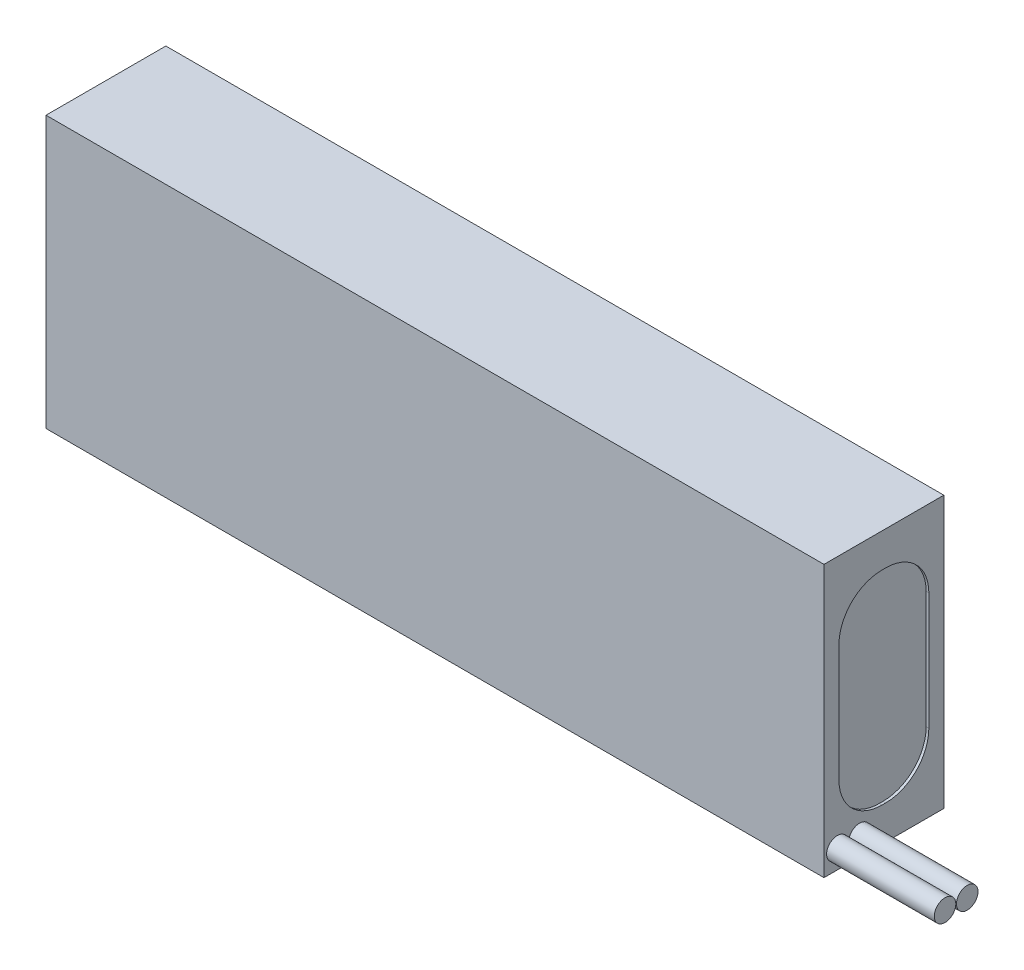
SolidWorks part; units mm, degrees
ref_plane "Front Plane" through (0, 0, 0) normal (0, 0, 1) x (1, 0, 0)
ref_plane "Top Plane" through (0, 0, 0) normal (0, 1, 0) x (1, 0, 0)
ref_plane "Right Plane" through (0, 0, 0) normal (1, 0, 0) x (0, 0, -1)
ref_plane "Plane1" through (0, 0, -15) normal (0, 0, -1) x (-1, 0, 0)
sketch "Sketch1" plane through (0, 0, -15) normal (0, 0, -1) x (-1, 0, 0)
  line L0 (-69, -22) -> (75.5, -22)
  line L1 (75.5, -22) -> (75.5, 28.4)
  line L2 (75.5, 28.4) -> (-69, 28.4)
  line L3 (-69, 28.4) -> (-69, -22)
  line L4 (-69, 3.2) -> (75.5, 3.2) construction
  line L5 (3.25, 28.4) -> (3.25, -22) construction
  dimension "D1" = 50.4
  dimension "D2" = 144.5
extrude "Boss-Extrude1" add sketch "Sketch1" against normal blind 22.26
sketch "Sketch2" plane through (69, 0, 0) normal (1, 0, 0) x (0, 0, -1)
  line L0 (-4.4775, 14.1) -> (-4.4775, -7.7)
  line L1 (3.5225, -15.7) -> (4.2175, -15.7)
  line L2 (12.2175, -7.7) -> (12.2175, 14.1)
  line L3 (4.2175, 22.1) -> (3.5225, 22.1)
  line L4 (-7.26, 28.4) -> (15, -22) construction
  line L5 (15, 28.4) -> (-7.26, -22) construction
  line L6 (-4.4775, 22.1) -> (12.2175, -15.7) construction
  line L7 (12.2175, 22.1) -> (-4.4775, -15.7) construction
  line L12 (-7.26, 28.4) -> (15, 28.4) construction
  line L13 (-7.26, 28.4) -> (-7.26, -22) construction
  line L14 (-7.26, -22) -> (15, -22) construction
  line L15 (15, 28.4) -> (15, -22) construction
  line L16 (-7.26, 28.4) -> (15, -22) construction
  line L17 (-7.26, -22) -> (15, 28.4) construction
  arc A0 (-4.4775, -7.7) -> (3.5225, -15.7) centre (3.5225, -7.7) ccw
  arc A1 (4.2175, -15.7) -> (12.2175, -7.7) centre (4.2175, -7.7) ccw
  arc A2 (12.2175, 14.1) -> (4.2175, 22.1) centre (4.2175, 14.1) ccw
  arc A3 (-4.4775, 14.1) -> (3.5225, 22.1) centre (3.5225, 14.1) cw
  point P16 (3.87, 3.2)
  dimension "D3" = 8
  dimension "D1" = 16.695
  dimension "D2" = 22.26
extrude "Cut-Extrude1" cut sketch "Sketch2" against normal blind 0.5
sketch "Sketch3" plane through (-75.5, 0, 0) normal (-1, 0, 0) x (0, 0, 1)
  line L0 (-3.5225, 22.1) -> (-4.2175, 22.1)
  line L1 (-12.2175, 14.1) -> (-12.2175, -7.7)
  line L2 (-4.2175, -15.7) -> (-3.5225, -15.7)
  line L3 (4.4775, -7.7) -> (4.4775, 14.1)
  line L4 (-12.2175, 22.1) -> (4.4775, -15.7) construction
  line L5 (4.4775, 22.1) -> (-12.2175, -15.7) construction
  line L6 (-15, 28.4) -> (7.26, -22) construction
  line L7 (7.26, -22) -> (-15, -22) construction
  line L8 (-15, -22) -> (7.26, 28.4) construction
  arc A0 (-12.2175, -7.7) -> (-4.2175, -15.7) centre (-4.2175, -7.7) ccw
  arc A1 (-3.5225, -15.7) -> (4.4775, -7.7) centre (-3.5225, -7.7) ccw
  arc A2 (-3.5225, 22.1) -> (4.4775, 14.1) centre (-3.5225, 14.1) cw
  arc A3 (-4.2175, 22.1) -> (-12.2175, 14.1) centre (-4.2175, 14.1) ccw
  dimension "D3" = 8
  dimension "D1" = 16.695
  dimension "D2" = 22.26
extrude "Cut-Extrude2" cut sketch "Sketch3" against normal blind 0.5
sketch "Sketch5" plane through (69, 0, 0) normal (1, 0, 0) x (0, 0, -1)
  circle A0 centre (-0.6514, -18.5346) radius 2
  dimension "D1" = 4
extrude "Boss-Extrude2" add sketch "Sketch5" along normal blind 20 contours A0
sketch "Sketch6" plane through (69, 0, 0) normal (1, 0, 0) x (0, 0, -1)
  circle A0 centre (-4.7748, -18.4596) radius 2
  dimension "D1" = 4
extrude "Boss-Extrude3" add sketch "Sketch6" along normal blind 20
equation "\"D1@Sketch3\"=\"D2@Sketch3\" * .75"
equation "\"D1@Sketch2\"=\"D2@Sketch2\"* .75"
